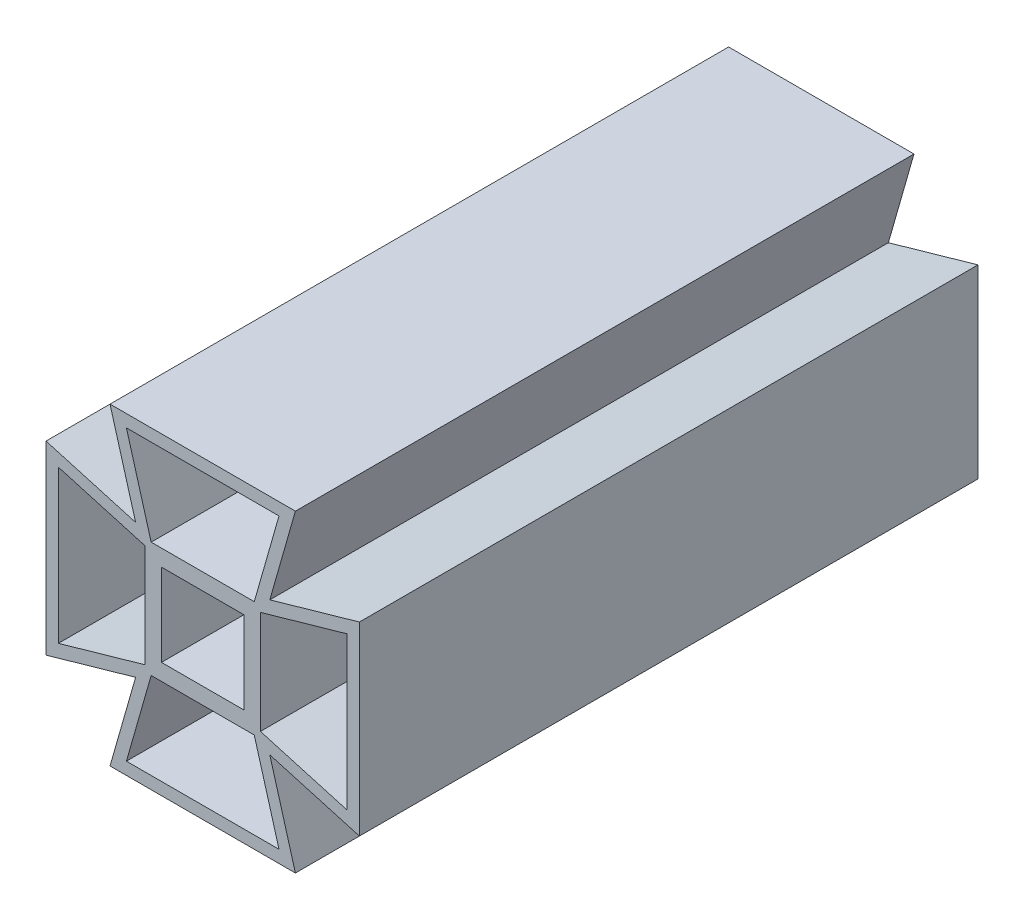
SolidWorks part; units mm, degrees
ref_plane "Front Plane" through (0, 0, 0) normal (0, 0, 1) x (1, 0, 0)
ref_plane "Top Plane" through (0, 0, 0) normal (0, 1, 0) x (1, 0, 0)
ref_plane "Right Plane" through (0, 0, 0) normal (1, 0, 0) x (0, 0, -1)
sketch "Sketch1" plane through (0, 0, 0) normal (0, 0, 1) x (1, 0, 0)
  line L0 (0, 45.5072) -> (0, -40.4348) construction
  line L1 (-48.8406, 0) -> (45.7971, 0) construction
  line L2 (12.5, 14) -> (-12.5, 14)
  line L3 (10, -10) -> (-10, -10)
  line L4 (10, -10) -> (10, 10)
  line L5 (10, 10) -> (-10, 10)
  line L6 (-10, -10) -> (-10, 10)
  line L7 (10, -10) -> (-10, 10) construction
  line L8 (10, 10) -> (-10, -10) construction
  line L13 (-12.5, 14) -> (-18.5, 35)
  line L14 (14, -12.5) -> (14, 12.5)
  line L15 (14, 12.5) -> (35, 18.5)
  line L16 (35, -18.5) -> (35, 18.5)
  line L17 (14, -12.5) -> (35, -18.5)
  line L18 (-12.5, -14) -> (12.5, -14)
  line L19 (12.5, -14) -> (18.5, -35)
  line L20 (-18.5, -35) -> (18.5, -35)
  line L21 (-12.5, -14) -> (-18.5, -35)
  line L22 (-14, 12.5) -> (-14, -12.5)
  line L23 (-14, -12.5) -> (-35, -18.5)
  line L24 (-35, 18.5) -> (-35, -18.5)
  line L25 (-14, 12.5) -> (-35, 18.5)
  line L26 (12.5, 14) -> (18.5, 35)
  line L27 (18.5, 35) -> (-18.5, 35)
  line L28 (22.4772, 38) -> (-22.4772, 38)
  line L32 (14.7629, 11) -> (-14.7629, 11) construction
  line L33 (38, -22.4772) -> (38, 22.4772)
  line L34 (16.2681, 16.2681) -> (38, 22.4772)
  line L35 (-16.2681, -16.2681) -> (-38, -22.4772)
  line L36 (-22.4772, -38) -> (22.4772, -38)
  line L37 (16.2681, -16.2681) -> (38, -22.4772)
  line L39 (-38, 22.4772) -> (-38, -22.4772)
  line L41 (16.2681, 16.2681) -> (22.4772, 38)
  line L42 (-16.2681, 16.2681) -> (-22.4772, 38)
  line L43 (-16.2681, 16.2681) -> (-38, 22.4772)
  line L44 (-14.7629, 11) -> (-22.4772, 38) construction
  line L46 (16.2681, -16.2681) -> (22.4772, -38)
  line L47 (14.7629, 11) -> (22.4772, 38) construction
  line L48 (-16.2681, -16.2681) -> (-22.4772, -38)
  point P5 (0, 0)
  point P10 (0, 0)
  point P13 (0, 14)
  point P14 (0, 35)
  point P19 (0, 35)
  dimension "D1" = 20
  dimension "D2" = 20
  dimension "D3" = 4
  dimension "D4" = 21
  dimension "D5" = 4
  dimension "D6" = 3
  dimension "D9" = 12.5
  dimension "D10" = 18.5
  dimension "D7" = 4
extrude "Boss-Extrude1" add sketch "Sketch1" along normal blind 150
sketch "Sketch2" plane through (0, 0, 0) normal (0, 0, 1) x (1, 0, 0)
  line L0 (0, 47.145) -> (0, -52.7539) construction
  line L1 (47.2966, 0) -> (-63.9717, 0) construction
  line L2 (18.5, 35) -> (-18.5, 35) construction
  line L3 (3.5, 35) -> (-3.5, 35)
  line L4 (3.5, 35) -> (3.5, 14)
  line L5 (3.5, 14) -> (-3.5, 14)
  line L6 (-3.5, 35) -> (-3.5, 14)
  line L7 (-12.5, 14) -> (12.5, 14) construction
  line L8 (35, -3.5) -> (14, -3.5)
  line L9 (35, -3.5) -> (35, 3.5)
  line L10 (35, 3.5) -> (14, 3.5)
  line L11 (14, -3.5) -> (14, 3.5)
  line L12 (-3.5, -35) -> (-3.5, -14)
  line L13 (-3.5, -35) -> (3.5, -35)
  line L14 (3.5, -35) -> (3.5, -14)
  line L15 (-3.5, -14) -> (3.5, -14)
  line L16 (-35, 3.5) -> (-14, 3.5)
  line L17 (-35, 3.5) -> (-35, -3.5)
  line L18 (-35, -3.5) -> (-14, -3.5)
  line L19 (-14, 3.5) -> (-14, -3.5)
  dimension "D1" = 7
  dimension "D2" = 3.5
  dimension "D3" = 4
extrude "Boss-Extrude2" add sketch "Sketch2" along normal blind 2
